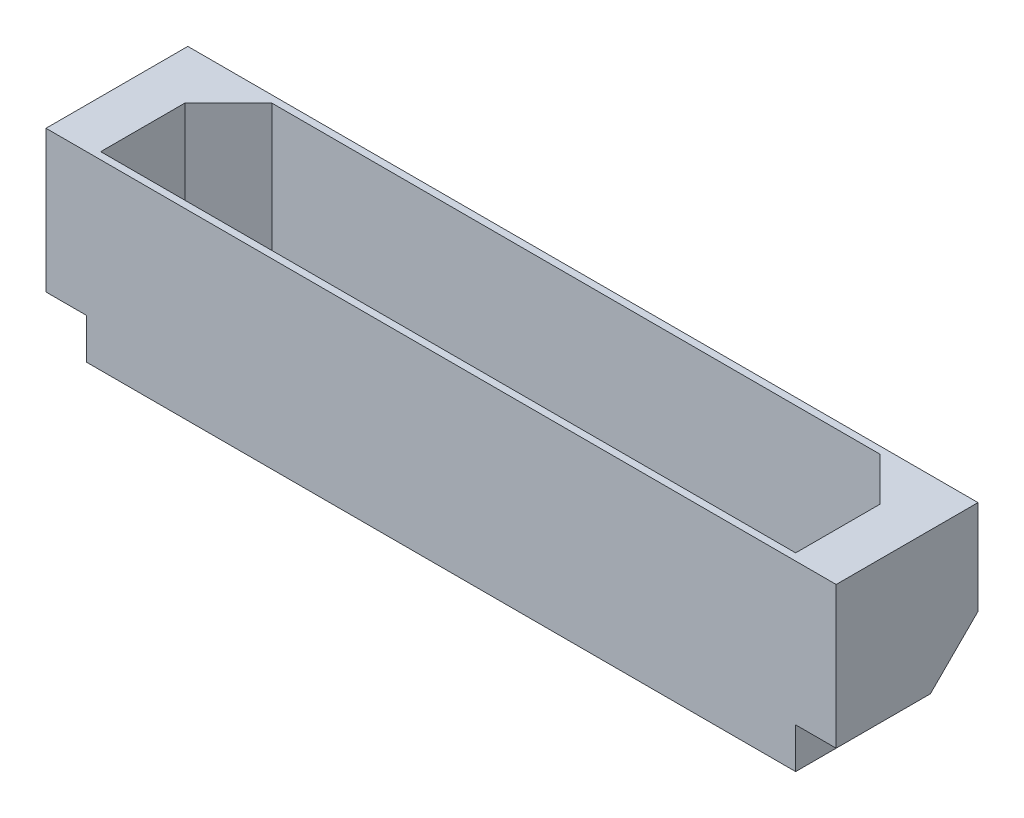
SolidWorks part; units mm, degrees
ref_plane "前基準面" through (0, 0, 0) normal (0, 0, 1) x (1, 0, 0)
ref_plane "上基準面" through (0, 0, 0) normal (0, 1, 0) x (1, 0, 0)
ref_plane "右基準面" through (0, 0, 0) normal (1, 0, 0) x (0, 0, -1)
sketch "草圖1" plane through (0, 0, 0) normal (0, 1, 0) x (1, 0, 0)
  line L1 (-195, -35) -> (195, -35)
  line L2 (-195, -35) -> (-195, 35)
  line L3 (-195, 35) -> (195, 35)
  line L4 (195, -35) -> (195, 35)
  line L5 (-195, -35) -> (195, 35) construction
  line L6 (-195, 35) -> (195, -35) construction
  point P0 (0, 0)
  dimension "D1" = 70
  dimension "D2" = 390
extrude "填料-伸長1" add sketch "草圖1" along normal blind 90
sketch "草圖2" plane through (0, 0, 35) normal (0, 0, 1) x (1, 0, 0)
  line L1 (195, 0) -> (175, 0)
  line L2 (195, 0) -> (195, 20)
  line L3 (195, 20) -> (175, 20)
  line L4 (175, 0) -> (175, 20)
  line L5 (-195, 0) -> (-175, 0)
  line L6 (-195, 0) -> (-195, 20)
  line L7 (-195, 20) -> (-175, 20)
  line L8 (-175, 0) -> (-175, 20)
  dimension "D1" = 20
  dimension "D2" = 20
  dimension "D3" = 20
  dimension "D4" = 20
extrude "除料-伸長1" cut sketch "草圖2" against normal blind 85
sketch "草圖3" plane through (195, 0, 0) normal (1, 0, 0) x (0, 0, -1)
  line L0 (35, 20) -> (11.5, 20)
  line L1 (35, 20) -> (-35, 20) construction
  line L2 (11.5, 20) -> (35, 43.5)
  line L3 (35, 90) -> (35, 20) construction
  line L4 (35, 43.5) -> (35, 20)
  dimension "D1" = 23.5
  dimension "D2" = 23.5
extrude "除料-伸長2" cut sketch "草圖3" against normal blind 20
mirror "鏡射1" about plane through (0, 0, 0) normal (1, 0, 0) of "除料-伸長2"
sketch "草圖4" plane through (0, 0, 0) normal (0, -1, 0) x (1, 0, 0)
  line L0 (-151.5, -35) -> (-175, -35)
  line L2 (175, -35) -> (-175, -35) construction
  line L3 (-175, -35) -> (-175, -11.5)
  line L4 (-175, -35) -> (-175, 35) construction
  line L5 (-175, -11.5) -> (-151.5, -35)
  line L6 (0, -46.75) -> (0, 46.75) construction
  line L7 (175, -11.5) -> (151.5, -35)
  line L8 (175, -35) -> (175, -11.5)
  line L9 (151.5, -35) -> (175, -35)
  dimension "D1" = 23.5
  dimension "D2" = 23.5
extrude "除料-伸長3" cut sketch "草圖4" against normal blind 20
sketch "草圖5" plane through (0, 90, 0) normal (0, 1, 0) x (1, 0, 0)
  line L0 (-171.5, 10.0503) -> (-171.5, -31.5)
  line L1 (-171.5, -31.5) -> (171.5, -31.5)
  line L2 (171.5, -31.5) -> (171.5, 10.0503)
  line L3 (171.5, 10.0503) -> (150.0503, 31.5)
  line L4 (150.0503, 31.5) -> (-150.0503, 31.5)
  line L5 (-150.0503, 31.5) -> (-171.5, 10.0503)
  line L6 (195, 35) -> (-195, 35) construction
  line L8 (175, 11.5) -> (175, -35) construction
  line L9 (175, 11.5) -> (151.5, 35) construction
  line L11 (-175, 11.5) -> (-175, -35) construction
  line L12 (-151.5, 35) -> (-175, 11.5) construction
  line L14 (-195, -35) -> (195, -35) construction
  dimension "D1" = 3.5
  dimension "D2" = 3.5
  dimension "D3" = 3.5
  dimension "D4" = 3.5
  dimension "D5" = 3.5
  dimension "D6" = 3.5
extrude "除料-伸長4" cut sketch "草圖5" against normal blind 86.5 contours L2 L3 L4 L5 L0 L1
